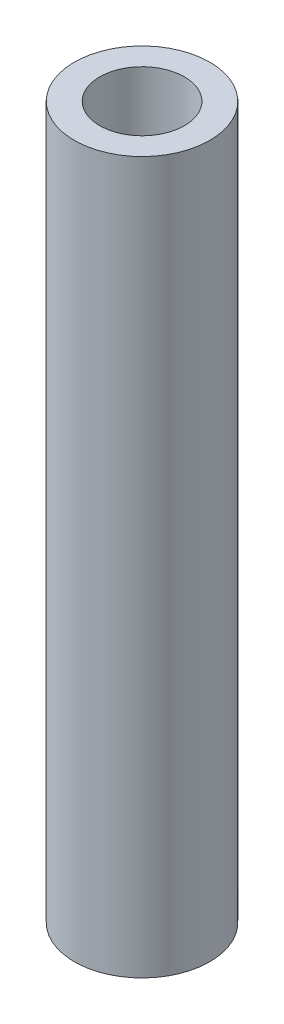
SolidWorks part; units mm, degrees
material "1060 合金"
ref_plane "前视基准面" through (0, 0, 0) normal (0, 0, 1) x (1, 0, 0)
ref_plane "上视基准面" through (0, 0, 0) normal (0, 1, 0) x (1, 0, 0)
ref_plane "右视基准面" through (0, 0, 0) normal (1, 0, 0) x (0, 0, -1)
sketch "草图1" plane through (0, 0, 0) normal (0, 1, 0) x (1, 0, 0)
  circle A0 centre (0, 0) radius 2
  circle A1 centre (0, 0) radius 1.25
  dimension "D1" = 4
  dimension "D2" = 2.5
sketch "草图2" plane through (0, 0, 0) normal (0, 1, 0) x (1, 0, 0)
  circle A0 centre (0, 0) radius 2
  circle A1 centre (0, 0) radius 1.25
  dimension "D1" = 4
  dimension "D2" = 2.5
extrude "凸台-拉伸1" add sketch "草图2" along normal blind 21
